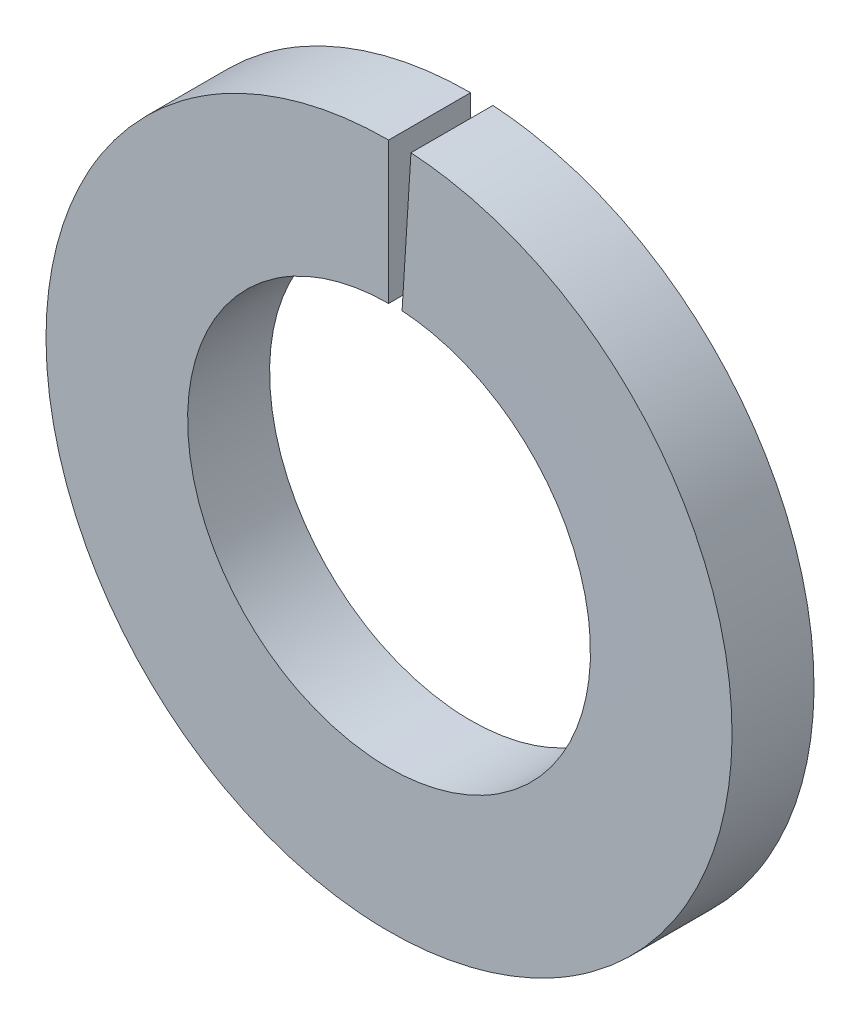
SolidWorks part; units mm, degrees
ref_plane "Front Plane" through (0, 0, 0) normal (0, 0, 1) x (1, 0, 0)
ref_plane "Top Plane" through (0, 0, 0) normal (0, 1, 0) x (1, 0, 0)
ref_plane "Right Plane" through (0, 0, 0) normal (1, 0, 0) x (0, 0, -1)
sketch "Sketch1" plane through (0, 0, 0) normal (0, 0, 1) x (1, 0, 0)
  line L0 (0, 4.6) -> (0, 2.7) construction
  circle A0 centre (0, 0) radius 4.6
  circle A1 centre (0, 0) radius 2.7 construction
  dimension "ID" = 5.4
  dimension "OD" = 9.2
curve "Helix/Spiral1" pitch 0.0111 height 0.011 turns 0.99 parameters "HT"=0.011
sketch "Sketch2" plane through (0, 0, 0) normal (1, 0, 0) x (0, 0, -1)
  line L1 (0, 4.6) -> (-1.1, 4.6)
  line L2 (0, 4.6) -> (0, 2.7)
  line L3 (0, 2.7) -> (-1.1, 2.7)
  line L4 (-1.1, 4.6) -> (-1.1, 2.7)
  dimension "THK" = 1.1
sweep "Sweep1" add profiles "Sketch2" path "Helix/Spiral1"
equation "\"HT@Helix/Spiral1\"= \"THK@Sketch2\" * 0.01"
